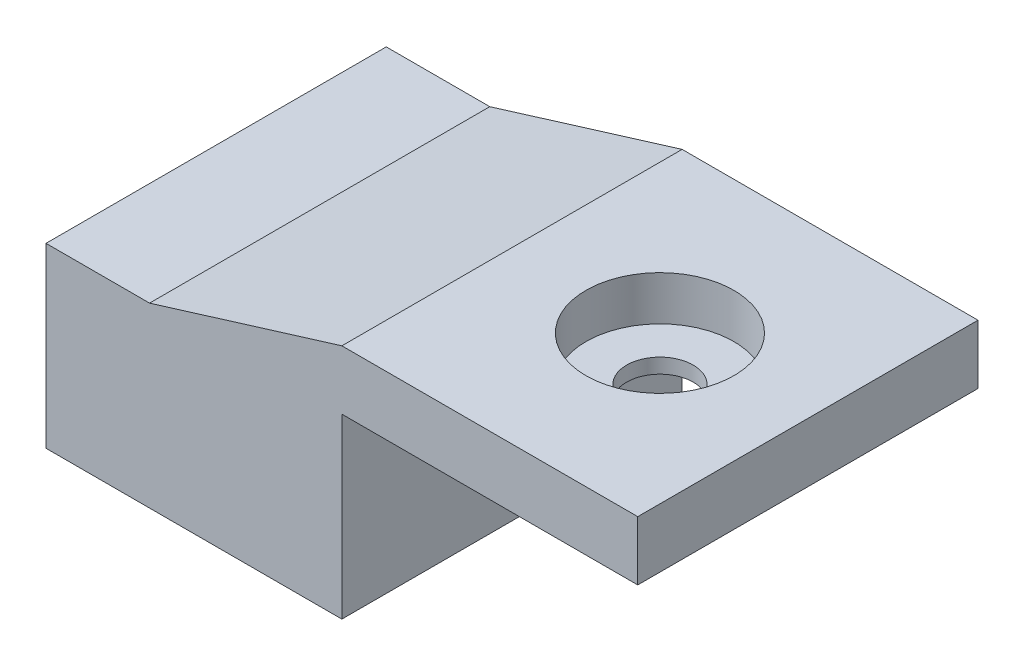
SolidWorks part; units mm, degrees
material "ABS"
ref_plane "Piano frontale" through (0, 0, 0) normal (0, 0, 1) x (1, 0, 0)
ref_plane "Piano superiore" through (0, 0, 0) normal (0, 1, 0) x (1, 0, 0)
ref_plane "Piano destro" through (0, 0, 0) normal (1, 0, 0) x (0, 0, -1)
sketch "Schizzo1" plane through (0, 0, 0) normal (0, 0, 1) x (1, 0, 0)
  line L0 (0, 0) -> (20, 0)
  line L1 (20, 0) -> (20, 12)
  line L2 (20, 12) -> (40, 12)
  line L3 (40, 12) -> (40, 16)
  line L4 (40, 16) -> (20, 16)
  line L6 (0, 12) -> (0, 0)
  line L7 (0, 12) -> (20, 12) construction
  line L8 (0, 12) -> (7, 12)
  line L9 (7, 12) -> (20, 16)
  line L10 (20, 12) -> (20, 16) construction
  dimension "D1" = 12
  dimension "D2" = 20
  dimension "D3" = 7
  dimension "D4" = 4
  dimension "D5" = 20
extrude "Estrusione-Estrusione1" add sketch "Schizzo1" along normal blind 23
hole_wizard "Foro per Vite M4-1" positions "Schizzo3D1" profile "Schizzo2" hole size "M4" standard "ISO"
sketch3d "Schizzo3D1"
  line L0 (0, 5.5, 5) -> (0, 5.5, 18) construction
  line L2 (0, 12, 23) -> (0, 12, 0) construction
  line L3 (0, 12, 0) -> (0, 0, 0) construction
  point P0 (0, 5.5, 5)
  point P2 (0, 5.5, 18)
  dimension "D1" = 13
  dimension "D2" = 6.5
  dimension "D3" = 5
sketch "Schizzo2" plane through (0, 5.5, 5) normal (0, 1, 0) x (0, 0, 1)
  line L0 (0, 0) -> (0, 11.6824)
  line L1 (0, 11.6824) -> (2.8, 10)
  line L2 (2.8, 10) -> (2.8, 0)
  line L5 (2.8, 0) -> (0, 0)
  line L10 (0, 11.6824) -> (-2.8, 10) construction
  line L11 (0, -6.35) -> (0, 107.95) construction
  dimension "Hole Dia." = 5.6
  dimension "Hole Depth" = 10
  dimension "Drill Angle" = 118
sketch "Schizzo3" plane through (0, 16, 0) normal (0, 1, 0) x (1, 0, 0)
  line L0 (20, 0) -> (40, -23) construction
  point P0 (30, -11.5)
  point P11 (30, -11.5)
hole_wizard "Foro lamato per Bullone M5 a testa esagonale-1" positions "Schizzo3" profile "Schizzo4" counterbore size "M5" standard "ISO"
sketch "Schizzo4" plane through (30, 16, 11.5) normal (1, 0, 0) x (0, 0, 1)
  line L0 (0, 0) -> (0, 11.3519)
  line L1 (0, 11.3519) -> (2.25, 10)
  line L2 (2.25, 10) -> (2.25, 3)
  line L3 (2.25, 3) -> (5, 3)
  line L4 (5, 3) -> (5, 0)
  line L5 (5, 0) -> (0, 0)
  line L10 (0, 11.3519) -> (-2.25, 10) construction
  line L11 (0, -6.35) -> (0, 107.95) construction
  dimension "Hole Dia." = 4.5
  dimension "Hole Depth" = 10
  dimension "C'Bore Dia." = 10
  dimension "C'Bore Depth" = 3
  dimension "Drill Angle" = 118
